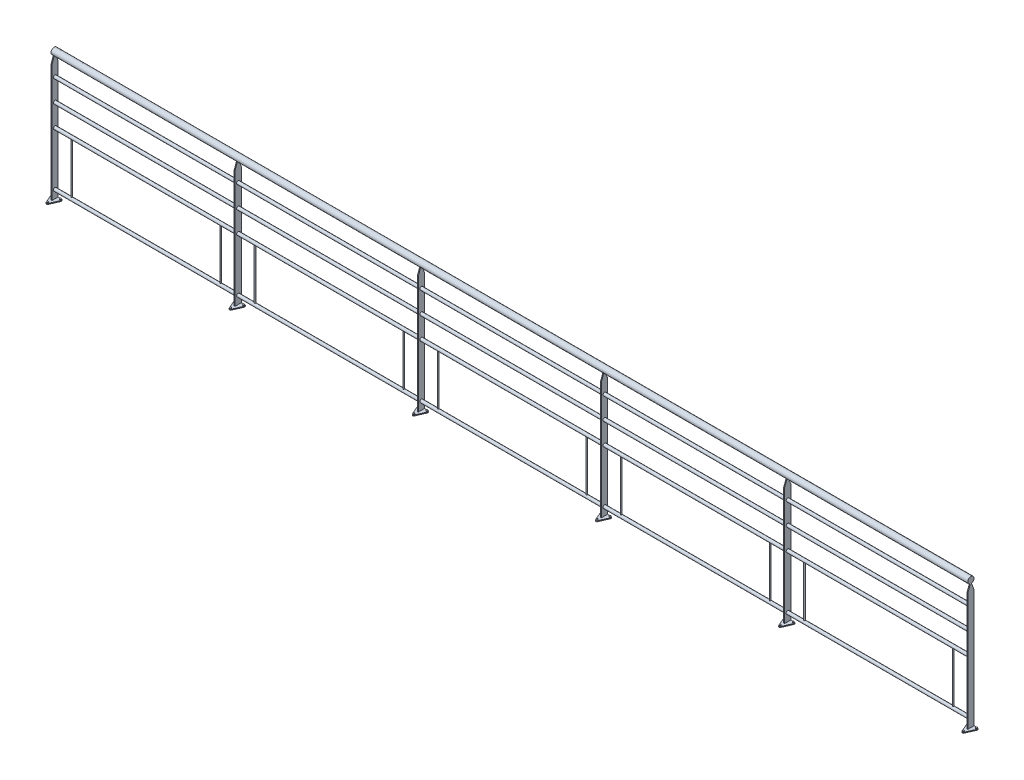
SolidWorks part; units mm, degrees
ref_plane "Plan de face" through (0, 0, 0) normal (0, 0, 1) x (1, 0, 0)
ref_plane "Plan de dessus" through (0, 0, 0) normal (0, 1, 0) x (1, 0, 0)
ref_plane "Plan de droite" through (0, 0, 0) normal (1, 0, 0) x (0, 0, -1)
sketch "Esquisse2" plane through (0, 0, 0) normal (1, 0, 0) x (0, 0, -1)
  line L0 (-25, 467.7526) -> (25, -467.7526) construction
  line L1 (-25, 467.7526) -> (25, 467.7526) construction
  line L2 (-25, 467.7526) -> (-25, -467.7526)
  line L3 (-25, -467.7526) -> (25, -467.7526)
  line L4 (25, 467.7526) -> (25, -467.7526)
  line L5 (-25, 467.7526) -> (-5, 522.7526)
  line L6 (-5, 522.7526) -> (5, 522.7526) construction
  line L7 (5, 522.7526) -> (25, 467.7526)
  arc A0 (5, 522.7526) -> (-5, 522.7526) centre (0, 547.2474) ccw construction
  arc A1 (-5, 522.7526) -> (5, 522.7526) centre (0, 547.2474) ccw
  point P9 (0, 522.2474)
  dimension "D5" = 50
  dimension "D1" = 990
  dimension "D2" = 50
  dimension "D3" = 55
  dimension "D4" = 10
extrude "Boss.-Extru.1" add sketch "Esquisse2" against normal blind 7285
sketch "Esquisse3" plane through (0, 0, 25) normal (0, 0, 1) x (1, 0, 0)
  line L0 (-7285, 522.7526) -> (0, 522.7526) construction
  line L1 (-7278, 522.7526) -> (-5829.4, 522.7526)
  line L2 (-7278, 522.7526) -> (-7278, -467.7526)
  line L3 (-7278, -467.7526) -> (-5829.4, -467.7526)
  line L4 (-5829.4, 522.7526) -> (-5829.4, -467.7526)
  line L5 (-7285, -467.7526) -> (0, -467.7526) construction
  line L6 (-7285, 467.7526) -> (-7285, -467.7526) construction
  line L7 (-7285, 522.7526) -> (-7278, 522.7526) construction
  line L8 (-7, 522.7526) -> (-1455.6, 522.7526)
  line L9 (-7, 522.7526) -> (-7, -467.7526)
  line L10 (-7, -467.7526) -> (-1455.6, -467.7526)
  line L11 (-1455.6, 522.7526) -> (-1455.6, -467.7526)
  line L12 (-1462.6, 522.7526) -> (-2911.2, 522.7526)
  line L13 (-1462.6, 522.7526) -> (-1462.6, -467.7526)
  line L14 (-1462.6, -467.7526) -> (-2911.2, -467.7526)
  line L15 (-2911.2, 522.7526) -> (-2911.2, -467.7526)
  line L16 (-2918.2, 522.7526) -> (-4366.8, 522.7526)
  line L17 (-2918.2, 522.7526) -> (-2918.2, -467.7526)
  line L18 (-2918.2, -467.7526) -> (-4366.8, -467.7526)
  line L19 (-4366.8, 522.7526) -> (-4366.8, -467.7526)
  line L20 (-4373.8, 522.7526) -> (-5822.4, 522.7526)
  line L21 (-4373.8, 522.7526) -> (-4373.8, -467.7526)
  line L22 (-4373.8, -467.7526) -> (-5822.4, -467.7526)
  line L23 (-5822.4, 522.7526) -> (-5822.4, -467.7526)
  line L24 (-5829.4, 522.7526) -> (-5822.4, 522.7526) construction
  line L25 (-4373.8, 522.7526) -> (-4366.8, 522.7526) construction
  line L26 (-2918.2, 522.7526) -> (-2911.2, 522.7526) construction
  line L27 (-1462.6, 522.7526) -> (-1455.6, 522.7526) construction
  line L28 (-7, 522.7526) -> (0, 522.7526) construction
  dimension "D1" = 7
extrude "Enlèv. mat.-Extru.1" cut sketch "Esquisse3" against normal through all
sketch "Esquisse4" plane through (0, 0, 0) normal (1, 0, 0) x (0, 0, -1)
  line L0 (-25, -467.7526) -> (25, -467.7526) construction
  line L1 (0, 372.2474) -> (0, 197.2474) construction
  line L2 (0, 197.2474) -> (0, 22.2474) construction
  line L3 (0, 22.2474) -> (0, -402.7526) construction
  line L4 (0, -402.7526) -> (0, -467.7526) construction
  circle A0 centre (0, 547.2474) radius 25
  arc A1 (-5, 522.7526) -> (5, 522.7526) centre (0, 547.2474) ccw construction
  circle A2 centre (0, -402.7526) radius 12.5
  circle A3 centre (0, 22.2474) radius 12.5
  circle A4 centre (0, 197.2474) radius 12.5
  circle A5 centre (0, 372.2474) radius 12.5
  dimension "D1" = 50
  dimension "D2" = 25
  dimension "D3" = 65
  dimension "D4" = 490
  dimension "D5" = 665
  dimension "D6" = 840
extrude "Boss.-Extru.2" add sketch "Esquisse4" against normal through all
sketch "Esquisse5" plane through (0, 0, 0) normal (0, 1, 0) x (1, 0, 0)
  line L0 (-7144.7, 0) -> (-7278, 0) construction
  line L1 (-7278, 25) -> (-7278, -25) construction
  line L2 (-5962.7, 0) -> (-5829.4, 0) construction
  line L3 (-5829.4, 25) -> (-5829.4, -25) construction
  line L4 (-5689.1, 0) -> (-5822.4, 0) construction
  line L5 (-4507.1, 0) -> (-4373.8, 0) construction
  line L6 (-4233.5, 0) -> (-4366.8, 0) construction
  line L7 (-3051.5, 0) -> (-2918.2, 0) construction
  line L8 (-2777.9, 0) -> (-2911.2, 0) construction
  line L9 (-1595.9, 0) -> (-1462.6, 0) construction
  line L10 (-1322.3, 0) -> (-1455.6, 0) construction
  line L11 (-140.3, 0) -> (-7, 0) construction
  line L12 (-7, 25) -> (-7, -25) construction
  circle A0 centre (-7144.7, 0) radius 4.5
  circle A1 centre (-5962.7, 0) radius 4.5
  circle A2 centre (-5689.1, 0) radius 4.5
  circle A3 centre (-4507.1, 0) radius 4.5
  circle A4 centre (-4233.5, 0) radius 4.5
  circle A5 centre (-3051.5, 0) radius 4.5
  circle A6 centre (-2777.9, 0) radius 4.5
  circle A7 centre (-1595.9, 0) radius 4.5
  circle A8 centre (-1322.3, 0) radius 4.5
  circle A9 centre (-140.3, 0) radius 4.5
  point P4 (-7140.2, 0)
  point P5 (-5967.2, 0)
  point P18 (-5684.6, 0)
  point P19 (-4511.6, 0)
  point P26 (-4229, 0)
  point P27 (-3056, 0)
  point P34 (-2773.4, 0)
  point P35 (-1600.4, 0)
  point P42 (-1317.8, 0)
  point P43 (-144.8, 0)
  dimension "D1" = 9
  dimension "D2" = 1173
  dimension "D3" = 5
extrude "Boss.-Extru.3" add sketch "Esquisse5" against normal up to next and the other way up to next
sketch "Esquisse6" plane through (0, -467.7526, 0) normal (0, -1, 0) x (1, 0, 0)
  line L0 (-7312.5388, -25) -> (-7250.4612, -25)
  line L1 (-7285, -25) -> (0, -25) construction
  line L2 (-7274, 60.0956) -> (-7242.2518, -12.4459)
  line L3 (-7289, 60.0956) -> (-7320.7482, -12.4459)
  line L5 (-7285, -25) -> (-7278, -25) construction
  line L6 (-7321.5, 65) -> (-7241.5, 65) construction
  line L7 (-7320.7482, -12.4459) -> (-7312.5388, -25) construction
  line L8 (-7242.2518, -12.4459) -> (-7250.4612, -25) construction
  line L9 (-7289, 60.0956) -> (-7274, 60.0956) construction
  line L10 (-5856.9388, -25) -> (-5794.8612, -25)
  line L11 (-5818.4, 60.0956) -> (-5786.6518, -12.4459)
  line L12 (-5833.4, 60.0956) -> (-5865.1482, -12.4459)
  line L13 (-5865.9, 65) -> (-5785.9, 65) construction
  line L14 (-5865.1482, -12.4459) -> (-5856.9388, -25) construction
  line L15 (-5786.6518, -12.4459) -> (-5794.8612, -25) construction
  line L16 (-5833.4, 60.0956) -> (-5818.4, 60.0956) construction
  line L17 (-4401.3388, -25) -> (-4339.2612, -25)
  line L18 (-4362.8, 60.0956) -> (-4331.0518, -12.4459)
  line L19 (-4377.8, 60.0956) -> (-4409.5482, -12.4459)
  line L20 (-4410.3, 65) -> (-4330.3, 65) construction
  line L21 (-4409.5482, -12.4459) -> (-4401.3388, -25) construction
  line L22 (-4331.0518, -12.4459) -> (-4339.2612, -25) construction
  line L23 (-4377.8, 60.0956) -> (-4362.8, 60.0956) construction
  line L24 (-2945.7388, -25) -> (-2883.6612, -25)
  line L25 (-2907.2, 60.0956) -> (-2875.4518, -12.4459)
  line L26 (-2922.2, 60.0956) -> (-2953.9482, -12.4459)
  line L27 (-2954.7, 65) -> (-2874.7, 65) construction
  line L28 (-2953.9482, -12.4459) -> (-2945.7388, -25) construction
  line L29 (-2875.4518, -12.4459) -> (-2883.6612, -25) construction
  line L30 (-2922.2, 60.0956) -> (-2907.2, 60.0956) construction
  line L31 (-1490.1388, -25) -> (-1428.0612, -25)
  line L32 (-1451.6, 60.0956) -> (-1419.8518, -12.4459)
  line L33 (-1466.6, 60.0956) -> (-1498.3482, -12.4459)
  line L34 (-1499.1, 65) -> (-1419.1, 65) construction
  line L35 (-1498.3482, -12.4459) -> (-1490.1388, -25) construction
  line L36 (-1419.8518, -12.4459) -> (-1428.0612, -25) construction
  line L37 (-1466.6, 60.0956) -> (-1451.6, 60.0956) construction
  line L38 (-34.5388, -25) -> (27.5388, -25)
  line L39 (4, 60.0956) -> (35.7482, -12.4459)
  line L40 (-11, 60.0956) -> (-42.7482, -12.4459)
  line L41 (-43.5, 65) -> (36.5, 65) construction
  line L42 (-42.7482, -12.4459) -> (-34.5388, -25) construction
  line L43 (35.7482, -12.4459) -> (27.5388, -25) construction
  line L44 (-11, 60.0956) -> (4, 60.0956) construction
  line L45 (-7, -25) -> (0, -25) construction
  arc A0 (-7289, 60.0956) -> (-7274, 60.0956) centre (-7281.5, 56.8132) cw
  arc A1 (-7250.4612, -25) -> (-7242.2518, -12.4459) centre (-7250.4612, -16.0388) ccw
  arc A2 (-7312.5388, -25) -> (-7320.7482, -12.4459) centre (-7312.5388, -16.0388) cw
  arc A3 (-5833.4, 60.0956) -> (-5818.4, 60.0956) centre (-5825.9, 56.8132) cw
  arc A4 (-5794.8612, -25) -> (-5786.6518, -12.4459) centre (-5794.8612, -16.0388) ccw
  arc A5 (-5856.9388, -25) -> (-5865.1482, -12.4459) centre (-5856.9388, -16.0388) cw
  arc A6 (-4377.8, 60.0956) -> (-4362.8, 60.0956) centre (-4370.3, 56.8132) cw
  arc A7 (-4339.2612, -25) -> (-4331.0518, -12.4459) centre (-4339.2612, -16.0388) ccw
  arc A8 (-4401.3388, -25) -> (-4409.5482, -12.4459) centre (-4401.3388, -16.0388) cw
  arc A9 (-2922.2, 60.0956) -> (-2907.2, 60.0956) centre (-2914.7, 56.8132) cw
  arc A10 (-2883.6612, -25) -> (-2875.4518, -12.4459) centre (-2883.6612, -16.0388) ccw
  arc A11 (-2945.7388, -25) -> (-2953.9482, -12.4459) centre (-2945.7388, -16.0388) cw
  arc A12 (-1466.6, 60.0956) -> (-1451.6, 60.0956) centre (-1459.1, 56.8132) cw
  arc A13 (-1428.0612, -25) -> (-1419.8518, -12.4459) centre (-1428.0612, -16.0388) ccw
  arc A14 (-1490.1388, -25) -> (-1498.3482, -12.4459) centre (-1490.1388, -16.0388) cw
  arc A15 (-11, 60.0956) -> (4, 60.0956) centre (-3.5, 56.8132) cw
  arc A16 (27.5388, -25) -> (35.7482, -12.4459) centre (27.5388, -16.0388) ccw
  arc A17 (-34.5388, -25) -> (-42.7482, -12.4459) centre (-34.5388, -16.0388) cw
  point P7 (-7281.5, -25)
  point P15 (-7321.5, -16.0388)
  point P16 (-7241.5, -16.0388)
  point P19 (-7281.5, 65)
  point P24 (-5825.9, -25)
  point P32 (-5865.9, -16.0388)
  point P33 (-5785.9, -16.0388)
  point P35 (-5825.9, 65)
  point P39 (-4370.3, -25)
  point P47 (-4410.3, -16.0388)
  point P48 (-4330.3, -16.0388)
  point P50 (-4370.3, 65)
  point P54 (-2914.7, -25)
  point P62 (-2954.7, -16.0388)
  point P63 (-2874.7, -16.0388)
  point P65 (-2914.7, 65)
  point P69 (-1459.1, -25)
  point P77 (-1499.1, -16.0388)
  point P78 (-1419.1, -16.0388)
  point P80 (-1459.1, 65)
  point P84 (-3.5, -25)
  point P92 (-43.5, -16.0388)
  point P93 (36.5, -16.0388)
  point P95 (-3.5, 65)
  dimension "D1" = 80
  dimension "D2" = 90
  dimension "D3" = 15
  dimension "D4" = 6
extrude "Boss.-Extru.4" add sketch "Esquisse6" along normal blind 7
sketch "Esquisse7" plane through (0, -467.7526, 0) normal (0, 1, 0) x (1, 0, 0)
  circle A0 centre (-7312.5388, 16.0388) radius 5.5
  circle A1 centre (-7250.4612, 16.0388) radius 5.5
  circle A2 centre (-7281.5, -56.8132) radius 5.5
  circle A3 centre (-5856.9388, 16.0388) radius 5.5
  circle A4 centre (-5794.8612, 16.0388) radius 5.5
  circle A5 centre (-5825.9, -56.8132) radius 5.5
  circle A6 centre (-4401.3388, 16.0388) radius 5.5
  circle A7 centre (-4339.2612, 16.0388) radius 5.5
  circle A8 centre (-4370.3, -56.8132) radius 5.5
  circle A9 centre (-2945.7388, 16.0388) radius 5.5
  circle A10 centre (-2883.6612, 16.0388) radius 5.5
  circle A11 centre (-2914.7, -56.8132) radius 5.5
  circle A12 centre (-1490.1388, 16.0388) radius 5.5
  circle A13 centre (-1428.0612, 16.0388) radius 5.5
  circle A14 centre (-1459.1, -56.8132) radius 5.5
  circle A15 centre (-34.5388, 16.0388) radius 5.5
  circle A16 centre (27.5388, 16.0388) radius 5.5
  circle A17 centre (-3.5, -56.8132) radius 5.5
  point P9 (27.5388, 16.0388)
  dimension "D1" = 11
  dimension "D2" = 6
extrude "Boss.-Extru.5" add sketch "Esquisse7" along normal blind 10
fillet "Congé1" radius 5.5 18 edges at (-7281.5, -457.7526, 62.3132) (-7250.4612, -457.7526, -10.5388) (-7312.5388, -457.7526, -10.5388) (-5794.8612, -457.7526, -10.5388) (-5825.9, -457.7526, 62.3132) (-5856.9388, -457.7526, -10.5388) (-4339.2612, -457.7526, -10.5388) (-4370.3, -457.7526, 62.3132) (-4401.3388, -457.7526, -10.5388) (-2883.6612, -457.7526, -10.5388) (-2914.7, -457.7526, 62.3132) (-2945.7388, -457.7526, -10.5388) (27.5388, -457.7526, -10.5388) (-3.5, -457.7526, 62.3132) (-34.5388, -457.7526, -10.5388) (-1428.0612, -457.7526, -10.5388) (-1490.1388, -457.7526, -10.5388) (-1459.1, -457.7526, 62.3132)
